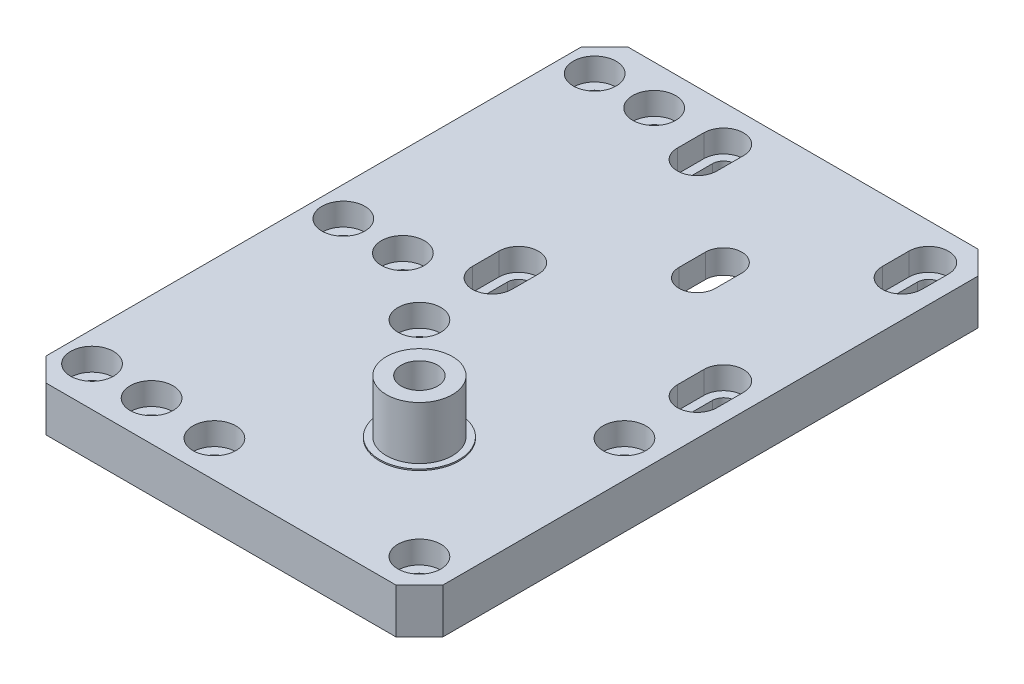
SolidWorks part; units mm, degrees
ref_plane "前视基准面" through (0, 0, 0) normal (0, 0, 1) x (1, 0, 0)
ref_plane "上视基准面" through (0, 0, 0) normal (0, 1, 0) x (1, 0, 0)
ref_plane "右视基准面" through (0, 0, 0) normal (1, 0, 0) x (0, 0, -1)
sketch "草图1" plane through (0, 0, 0) normal (0, 1, 0) x (1, 0, 0)
  line L0 (-58.5815, 0) -> (61.1555, 0) construction
  line L5 (0, 59.114) -> (0, -56.3447) construction
  line L7 (-18, 46) -> (42, 46)
  line L8 (-18, 46) -> (-18, -42)
  line L9 (-18, -42) -> (42, -42)
  line L10 (42, 46) -> (42, -42)
  dimension "D1" = 46
  dimension "D2" = 42
  dimension "D3" = 42
  dimension "D4" = 18
extrude "凸台-拉伸1" add sketch "草图1" along normal blind 6.8
sketch "草图2" plane through (0, 0, 0) normal (0, 1, 0) x (1, 0, 0)
  line L0 (-76.4156, 0) -> (115.4429, 0) construction
  line L1 (0, 65.3547) -> (0, -44.5285) construction
  line L2 (21, 58.9634) -> (21, -44.5285) construction
  line L3 (7.5121, -21) -> (43.5064, -21) construction
  line L4 (-76.4156, -21) -> (43.5064, -21) construction
  line L5 (21, 70.2679) -> (21, -44.5285) construction
  line L6 (8.4771, 21) -> (43.5064, 21) construction
  line L7 (-76.4156, 21) -> (43.5064, 21) construction
  line L8 (-76.4156, 0) -> (43.5064, 0) construction
  line L9 (8.4771, 25) -> (43.5064, 25) construction
  line L10 (21, 21) -> (21, 25) construction
  line L11 (18.25, 21) -> (18.25, 25)
  line L12 (23.75, 21) -> (23.75, 25)
  line L13 (7.2583, 25) -> (43.5064, 25) construction
  line L14 (7.2583, 21) -> (43.5064, 21) construction
  line L15 (0, 70.2679) -> (0, -44.5285) construction
  circle A0 centre (21, -21) radius 2.75
  arc A2 (18.25, 21) -> (23.75, 21) centre (21, 21) ccw
  arc A3 (23.75, 25) -> (18.25, 25) centre (21, 25) ccw
  point P18 (21, 23)
  point P27 (7.5121, -21)
  point P29 (43.5064, -21)
  point P31 (0, 0)
  point P32 (0, 0)
  point P34 (0, 0)
  dimension "D3" = 5.5
  dimension "D6" = 5.5
  dimension "D1" = 21
  dimension "D2" = 21
  dimension "D4" = 21
  dimension "D5" = 4
extrude "切除-拉伸6" cut sketch "草图2" along normal through all
sketch "草图3" plane through (0, 0, 0) normal (0, -1, 0) x (1, 0, 0)
  line L0 (21, -21) -> (21, -25) construction
  line L1 (32.05, -21) -> (32.05, -25)
  line L2 (9.95, -21) -> (9.95, -25)
  circle A0 centre (21, 21) radius 11.05
  arc A1 (32.05, -21) -> (9.95, -21) centre (21, -21) ccw
  arc A2 (9.95, -25) -> (32.05, -25) centre (21, -25) ccw
  point P7 (21, -23)
  dimension "D1" = 22.1
  dimension "D2" = 22.1
extrude "切除-拉伸7" cut sketch "草图3" against normal blind 3.2
sketch "草图4" plane through (0, 6.8, 0) normal (0, 1, 0) x (1, 0, 0)
  circle A0 centre (21, -21) radius 4.99
  circle A1 centre (21, -21) radius 2.75 construction
  circle A2 centre (21, -21) radius 2.75
  dimension "D1" = 9.98
extrude "凸台-拉伸2" add sketch "草图4" along normal blind 8.2
sketch "草图5" plane through (0, 6.8, 0) normal (0, 1, 0) x (1, 0, 0)
  circle A0 centre (21, -21) radius 4
  circle A1 centre (21, -21) radius 6
  dimension "D1" = 8
  dimension "D2" = 12
extrude "轴承限位" add sketch "草图5" along normal blind 0.2
sketch "草图6" plane through (0, 6.8, 0) normal (0, 1, 0) x (1, 0, 0)
  line L0 (7.5121, -21) -> (43.5064, -21) construction
  line L1 (7.5121, -21) -> (43.5064, -21) construction
  line L2 (-76.4156, 0) -> (115.4429, 0) construction
  line L3 (36.5, 18.3995) -> (36.5, -44.5285) construction
  line L4 (5.5, 65.3547) -> (5.5, -44.5285)
  line L5 (5.5, 18.3995) -> (5.5, -44.5285) construction
  line L6 (-1.4673, -36.5) -> (39.986, -36.5) construction
  line L7 (-1.4673, -36.5) -> (11.7091, -36.5) construction
  line L8 (-1.4673, -5.5) -> (38.9315, -5.5) construction
  line L9 (-1.4673, -5.5) -> (11.7091, -5.5) construction
  line L13 (-76.4156, -36) -> (3.5032, -36) construction
  line L14 (-76.4156, 40) -> (3.5032, 40) construction
  line L15 (-76.4156, 2) -> (3.5032, 2) construction
  line L17 (-13.5, 65.3547) -> (-13.5, -44.5285) construction
  line L18 (-4.5, 65.3547) -> (-4.5, -44.5285)
  line L19 (-4.5, 65.3547) -> (-4.5, -44.5285) construction
  circle A0 centre (5.5, -5.5) radius 1.5
  circle A3 centre (36.5, -5.5) radius 1.5
  circle A4 centre (36.5, -36.5) radius 1.5
  circle A5 centre (5.5, -36.5) radius 1.5
  circle A6 centre (-4.5, 40) radius 1.5
  circle A7 centre (-13.5, 40) radius 1.5
  circle A8 centre (-13.5, 2) radius 1.5
  circle A9 centre (-13.5, -36) radius 1.5
  circle A10 centre (-4.5, 2) radius 1.5
  circle A11 centre (-4.5, -36) radius 1.5
  point P0 (5.5, -5.5)
  point P13 (36.5, -5.5)
  point P19 (-4.5, 40)
  point P23 (36.5, -36.5)
  point P25 (5.5, -36.5)
  point P32 (-13.5, 40)
  point P34 (-13.5, 2)
  point P41 (-13.5, -36)
  point P45 (-4.5, 2)
  point P47 (-4.5, -36)
  dimension "D4" = 3
  dimension "D6" = 3
  dimension "D12" = 3
  dimension "D1" = 5.5
  dimension "D7" = 2
  dimension "D2" = 5.5
  dimension "D3" = 31
  dimension "D5" = 31
  dimension "D8" = 38
  dimension "D9" = 38
  dimension "D10" = 4.5
  dimension "D11" = 9
  dimension "D13" = 2
  dimension "D14" = 3
hole_wizard "M3 六角凹头螺钉的柱形沉头孔2" positions "草图6" profile "草图8" counterbore size "M3" standard "ISO"
sketch "草图8" plane through (5.5, 6.8, 5.5) normal (1, 0, 0) x (0, 0, 1)
  line L0 (0, 0) -> (0, 26.0215)
  line L1 (0, 26.0215) -> (1.7, 25)
  line L2 (1.7, 25) -> (1.7, 3.415)
  line L3 (1.7, 3.415) -> (1.725, 3.4)
  line L4 (1.725, 3.4) -> (3.25, 3.4)
  line L5 (3.25, 3.4) -> (3.25, 0)
  line L6 (3.25, 0) -> (0, 0)
  line L9 (-1.7, 3.415) -> (-1.725, 3.4) construction
  line L10 (0, 26.0215) -> (-1.7, 25) construction
  line L11 (0, -6.35) -> (0, 107.95) construction
  dimension "孔直径" = 3.4
  dimension "孔深度" = 25
  dimension "柱形沉头孔直径" = 6.5
  dimension "柱形沉头孔深度" = 3.4
  dimension "中间锥形沉头孔直径" = 3.45
  dimension "中间锥形沉头孔角度" = 118
  dimension "导头角度" = 118
sketch "草图9" plane through (0, 6.8, 0) normal (0, 1, 0) x (1, 0, 0)
  line L2 (-76.4156, 5.5) -> (115.4429, 5.5)
  line L3 (1.6962, 5.5) -> (40.3913, 5.5) construction
  line L4 (36.5, 65.3547) -> (36.5, 1.1212) construction
  line L5 (5.5, 65.3547) -> (5.5, -44.5285)
  line L6 (5.5, 65.3547) -> (5.5, 1.1212) construction
  line L7 (1.6962, 36.5) -> (40.3913, 36.5) construction
  line L8 (5.5, 5.5) -> (5.5, 9.5) construction
  line L9 (3.8, 5.5) -> (3.8, 9.5)
  line L10 (7.2, 5.5) -> (7.2, 9.5)
  line L11 (36.5, 5.5) -> (36.5, 9.5) construction
  line L12 (34.8, 5.5) -> (34.8, 9.5)
  line L13 (38.2, 5.5) -> (38.2, 9.5)
  line L14 (36.5, 36.5) -> (36.5, 40.5) construction
  line L15 (34.8, 36.5) -> (34.8, 40.5)
  line L16 (38.2, 36.5) -> (38.2, 40.5)
  line L17 (5.5, 36.5) -> (5.5, 40.5) construction
  line L18 (3.8, 36.5) -> (3.8, 40.5)
  line L19 (7.2, 36.5) -> (7.2, 40.5)
  arc A0 (3.8, 5.5) -> (7.2, 5.5) centre (5.5, 5.5) ccw
  arc A1 (7.2, 9.5) -> (3.8, 9.5) centre (5.5, 9.5) ccw
  arc A2 (34.8, 5.5) -> (38.2, 5.5) centre (36.5, 5.5) ccw
  arc A3 (38.2, 9.5) -> (34.8, 9.5) centre (36.5, 9.5) ccw
  arc A4 (34.8, 36.5) -> (38.2, 36.5) centre (36.5, 36.5) ccw
  arc A5 (38.2, 40.5) -> (34.8, 40.5) centre (36.5, 40.5) ccw
  arc A6 (3.8, 36.5) -> (7.2, 36.5) centre (5.5, 36.5) ccw
  arc A7 (7.2, 40.5) -> (3.8, 40.5) centre (5.5, 40.5) ccw
  point P13 (5.5, 7.5)
  point P18 (5.5, 38.4488)
  point P19 (5.5, 36.5)
  point P20 (36.5, 5.5)
  point P23 (36.5, 7.5)
  point P30 (36.5, 38.5)
  point P37 (5.5, 38.5)
  point P42 (36.5, 36.5)
  dimension "D8" = 3.4
  dimension "D5" = 4
  dimension "D1" = 5.5
  dimension "D2" = 5.5
  dimension "D3" = 31
  dimension "D4" = 31
  dimension "D6" = 2
  dimension "D7" = 2
extrude "切除-拉伸8" cut sketch "草图9" against normal through all
sketch "草图10" plane through (0, 6.8, 0) normal (0, 1, 0) x (1, 0, 0)
  line L0 (5.5, 5.5) -> (5.5, 9.5) construction
  line L1 (2.5, 5.5) -> (2.5, 9.5)
  line L2 (8.5, 5.5) -> (8.5, 9.5)
  line L3 (36.5, 5.5) -> (36.5, 9.5) construction
  line L4 (33.5, 5.5) -> (33.5, 9.5)
  line L5 (34.8, 9.5) -> (34.8, 5.5)
  line L6 (38.2, 5.5) -> (38.2, 9.5)
  line L7 (34.8, 9.5) -> (34.8, 5.5)
  line L8 (38.2, 5.5) -> (38.2, 9.5)
  line L9 (7.2, 5.5) -> (7.2, 9.5)
  line L10 (3.8, 9.5) -> (3.8, 5.5)
  line L11 (7.2, 5.5) -> (7.2, 9.5)
  line L12 (3.8, 9.5) -> (3.8, 5.5)
  line L13 (3.8, 40.5) -> (3.8, 36.5)
  line L14 (7.2, 36.5) -> (7.2, 40.5)
  line L15 (3.8, 40.5) -> (3.8, 36.5)
  line L16 (7.2, 36.5) -> (7.2, 40.5)
  line L17 (38.2, 36.5) -> (38.2, 40.5)
  line L18 (34.8, 40.5) -> (34.8, 36.5)
  line L19 (38.2, 36.5) -> (38.2, 40.5)
  line L20 (34.8, 40.5) -> (34.8, 36.5)
  line L21 (39.5, 5.5) -> (39.5, 9.5)
  line L22 (36.5, 36.5) -> (36.5, 40.5) construction
  line L23 (33.5, 36.5) -> (33.5, 40.5)
  line L24 (39.5, 36.5) -> (39.5, 40.5)
  line L25 (5.5, 36.5) -> (5.5, 40.5) construction
  line L26 (2.5, 36.5) -> (2.5, 40.5)
  line L27 (8.5, 36.5) -> (8.5, 40.5)
  arc A0 (2.5, 5.5) -> (8.5, 5.5) centre (5.5, 5.5) ccw
  arc A1 (8.5, 9.5) -> (2.5, 9.5) centre (5.5, 9.5) ccw
  arc A2 (33.5, 5.5) -> (39.5, 5.5) centre (36.5, 5.5) ccw
  arc A3 (39.5, 9.5) -> (33.5, 9.5) centre (36.5, 9.5) ccw
  arc A4 (38.2, 9.5) -> (34.8, 9.5) centre (36.5, 9.5) ccw
  arc A5 (34.8, 5.5) -> (38.2, 5.5) centre (36.5, 5.5) ccw
  arc A6 (38.2, 9.5) -> (34.8, 9.5) centre (36.5, 9.5) ccw
  arc A7 (34.8, 5.5) -> (38.2, 5.5) centre (36.5, 5.5) ccw
  arc A8 (7.2, 9.5) -> (3.8, 9.5) centre (5.5, 9.5) ccw
  arc A9 (3.8, 5.5) -> (7.2, 5.5) centre (5.5, 5.5) ccw
  arc A10 (7.2, 9.5) -> (3.8, 9.5) centre (5.5, 9.5) ccw
  arc A11 (3.8, 5.5) -> (7.2, 5.5) centre (5.5, 5.5) ccw
  arc A12 (7.2, 40.5) -> (3.8, 40.5) centre (5.5, 40.5) ccw
  arc A13 (3.8, 36.5) -> (7.2, 36.5) centre (5.5, 36.5) ccw
  arc A14 (7.2, 40.5) -> (3.8, 40.5) centre (5.5, 40.5) ccw
  arc A15 (3.8, 36.5) -> (7.2, 36.5) centre (5.5, 36.5) ccw
  arc A16 (38.2, 40.5) -> (34.8, 40.5) centre (36.5, 40.5) ccw
  arc A17 (34.8, 36.5) -> (38.2, 36.5) centre (36.5, 36.5) ccw
  arc A18 (38.2, 40.5) -> (34.8, 40.5) centre (36.5, 40.5) ccw
  arc A19 (34.8, 36.5) -> (38.2, 36.5) centre (36.5, 36.5) ccw
  arc A20 (33.5, 36.5) -> (39.5, 36.5) centre (36.5, 36.5) ccw
  arc A21 (39.5, 40.5) -> (33.5, 40.5) centre (36.5, 40.5) ccw
  arc A22 (2.5, 36.5) -> (8.5, 36.5) centre (5.5, 36.5) ccw
  arc A23 (8.5, 40.5) -> (2.5, 40.5) centre (5.5, 40.5) ccw
  point P4 (5.5, 7.5)
  point P15 (36.5, 36.5)
  point P23 (8.5, 7.5)
  point P34 (5.5, 36.5)
  point P39 (36.5, 7.5)
  point P46 (36.5, 38.5)
  point P53 (5.5, 38.5)
  dimension "D5" = 6
  dimension "D1" = 0
  dimension "D2" = 0
  dimension "D3" = 0
  dimension "D4" = 0
  dimension "D6" = 2
  dimension "D7" = 2
extrude "切除-拉伸9" cut sketch "草图10" against normal blind 3.4
chamfer "倒角1" distance 3.5355 angle 45 4 edges at (42, 3.4, -46) (42, 3.4, 42) (-18, 3.4, 42) (-18, 3.4, -46)
